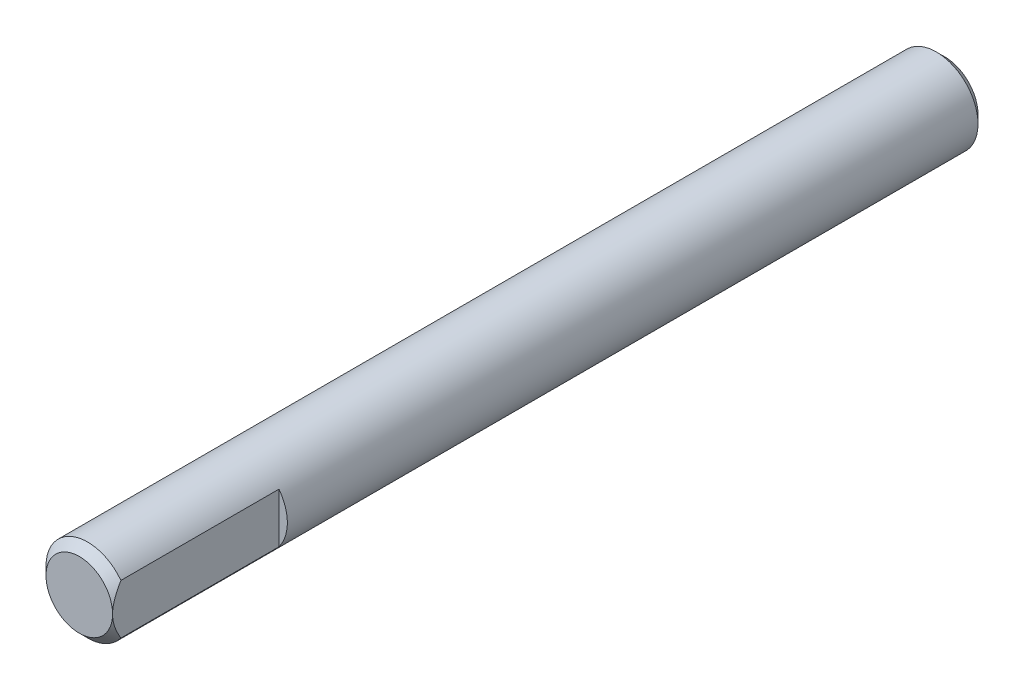
SolidWorks part; units mm, degrees
ref_plane "Front Plane" through (0, 0, 0) normal (0, 0, 1) x (1, 0, 0)
ref_plane "Top Plane" through (0, 0, 0) normal (0, 1, 0) x (1, 0, 0)
ref_plane "Right Plane" through (0, 0, 0) normal (1, 0, 0) x (0, 0, -1)
sketch "Sketch1" plane through (0, 0, 0) normal (0, 0, 1) x (1, 0, 0)
  circle A0 centre (0, 0) radius 2.5
  dimension "D1" = 5
extrude "Boss-Extrude1" add sketch "Sketch1" along normal blind 52
chamfer "Chamfer1" distance 0.5 angle 45 2 edges at (2.5, 0, 52) (2.5, 0, 0)
sketch "Sketch2" plane through (0, 0, 52) normal (0, 0, 1) x (1, 0, 0)
  line L0 (2, 2.0634) -> (2, -2.0203)
  line L1 (2, 2.0634) -> (4.4823, -2.128)
  line L2 (4.4823, -2.128) -> (3.1678, -2.4405)
  line L3 (3.1678, -2.4405) -> (2, -2.0203)
  dimension "D1" = 2
extrude "Cut-Extrude1" cut sketch "Sketch2" against normal blind 10
